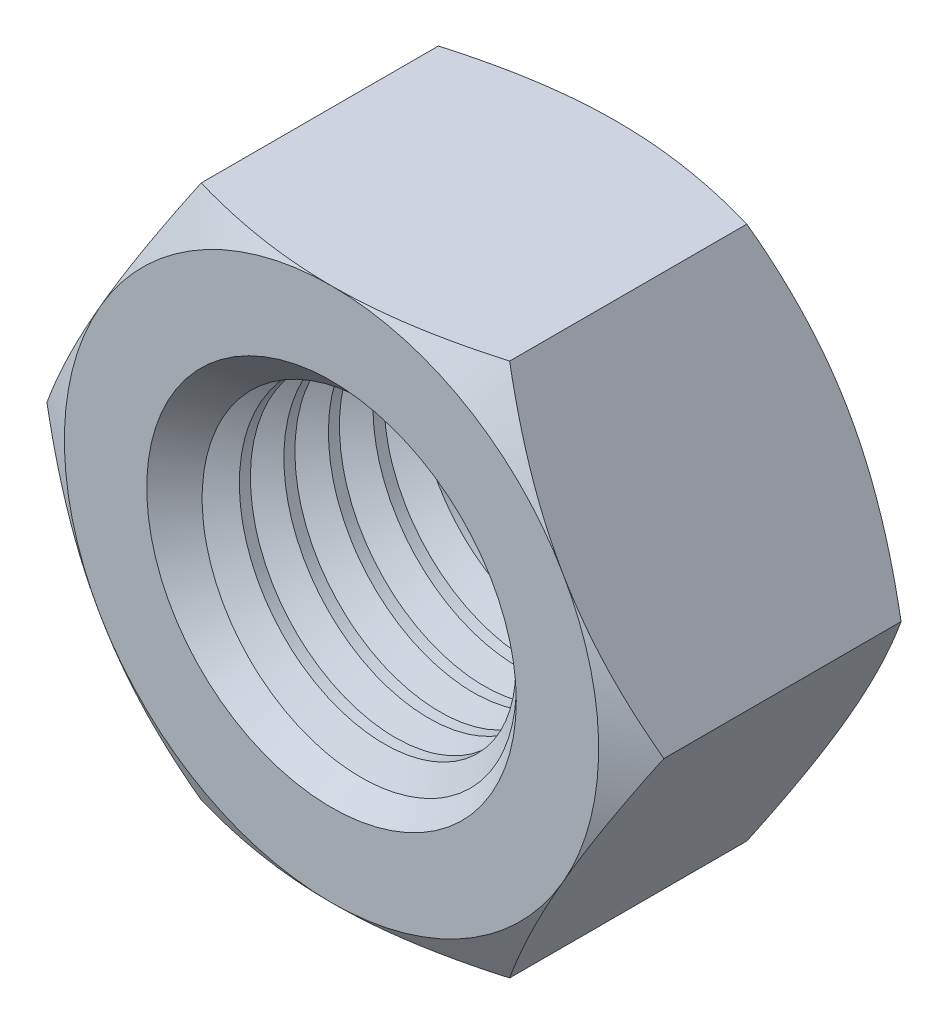
SolidWorks part; units mm, degrees
ref_plane "Front" through (0, 0, 0) normal (0, 0, 1) x (1, 0, 0)
ref_plane "Top" through (0, 0, 0) normal (0, 1, 0) x (1, 0, 0)
ref_plane "Right" through (0, 0, 0) normal (1, 0, 0) x (0, 0, -1)
sketch "Çizim1" plane through (0, 0, 0) normal (0, 0, 1) x (1, 0, 0)
  line L1 (17.3205, 0) -> (8.6603, 15)
  line L2 (8.6603, 15) -> (-8.6603, 15)
  line L3 (-8.6603, 15) -> (-17.3205, 0)
  line L4 (-17.3205, 0) -> (-8.6603, -15)
  line L5 (-8.6603, -15) -> (8.6603, -15)
  line L6 (8.6603, -15) -> (17.3205, 0)
  circle A0 centre (0, 0) radius 15 construction
  dimension "D1" = 30
extrude "Yükseklik-Ekstrüzyon1" add sketch "Çizim1" along normal blind 16
sketch "Çizim2" plane through (0, 0, 16) normal (0, 0, 1) x (1, 0, 0)
  circle A0 centre (0, 0) radius 15
extrude "Kes-Ekstrüzyon1" cut sketch "Çizim2" against normal blind 16 draft 60 flip side to cut
sketch "Çizim3" plane through (0, 0, 0) normal (0, 0, -1) x (-1, 0, 0)
  circle A0 centre (0, 0) radius 15
extrude "Kes-Ekstrüzyon2" cut sketch "Çizim3" against normal blind 16 draft 60 flip side to cut
sketch "Çizim4" plane through (0, 0, 0) normal (0, 0, -1) x (-1, 0, 0)
  circle A0 centre (0, 0) radius 8.375
  dimension "D1" = 16.75
extrude "Kes-Ekstrüzyon3" cut sketch "Çizim4" against normal blind 16
chamfer "Pah1" distance 2 angle 45 2 edges at (-8.375, 0, 16) (-8.375, 0, 0)
sketch "Çizim5" plane through (0, 0, 0) normal (0, 0, -1) x (-1, 0, 0)
  circle A0 centre (0, 0) radius 8.375
  dimension "D1" = 16.75
curve "Helis/Spiral1" pitch 2.5 height 19 turns 7.6
ref_plane "Düzlem1" through (-6.7755, -4.9227, 19) normal (0.5871, -0.8081, 0.0475) x (-0.8095, -0.5861, 0.0344)
sketch "Çizim6" plane through (-6.7755, -4.9227, 19) normal (0.5871, -0.8081, 0.0475) x (-0.8095, -0.5861, 0.0344)
  line L0 (-0.4989, -1.2262) -> (-0.4989, 1.2262)
  line L1 (1.625, 0) -> (-0.4989, 1.2262)
  line L3 (-0.4989, -1.2262) -> (1.625, 0)
  line L5 (-0.8125, 1.4073) -> (-0.8125, 0) [skipped]
  circle A0 centre (0, 0) radius 0.8125 construction
  dimension "D1" = 1.625
sweep "Kes-Süpür1" cut profiles "Çizim6" path "Helis/Spiral1"
